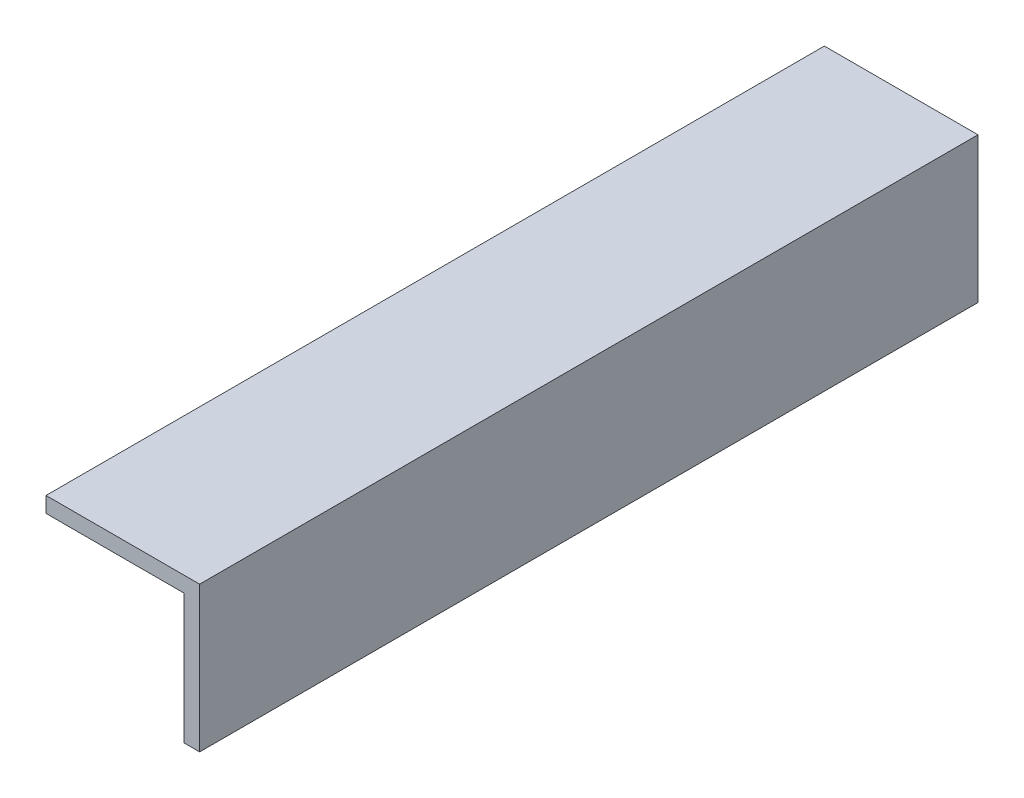
SolidWorks part; units mm, degrees
ref_plane "Front Plane" through (0, 0, 0) normal (0, 0, 1) x (1, 0, 0)
ref_plane "Top Plane" through (0, 0, 0) normal (0, 1, 0) x (1, 0, 0)
ref_plane "Right Plane" through (0, 0, 0) normal (1, 0, 0) x (0, 0, -1)
sketch "Sketch1" plane through (0, 0, 0) normal (0, 0, 1) x (1, 0, 0)
  line L0 (0, 0) -> (29.6072, 0)
  line L1 (29.6072, 0) -> (29.6072, -28)
  line L2 (0, 0) -> (0, -3)
  line L3 (0, -3) -> (26.6072, -3)
  line L4 (29.6072, -28) -> (26.6072, -28)
  line L5 (26.6072, -28) -> (26.6072, -3)
  dimension "D1" = 3
  dimension "D2" = 3
  dimension "D3" = 90
  dimension "D4" = 25
extrude "Boss-Extrude1" add sketch "Sketch1" along normal blind 150
